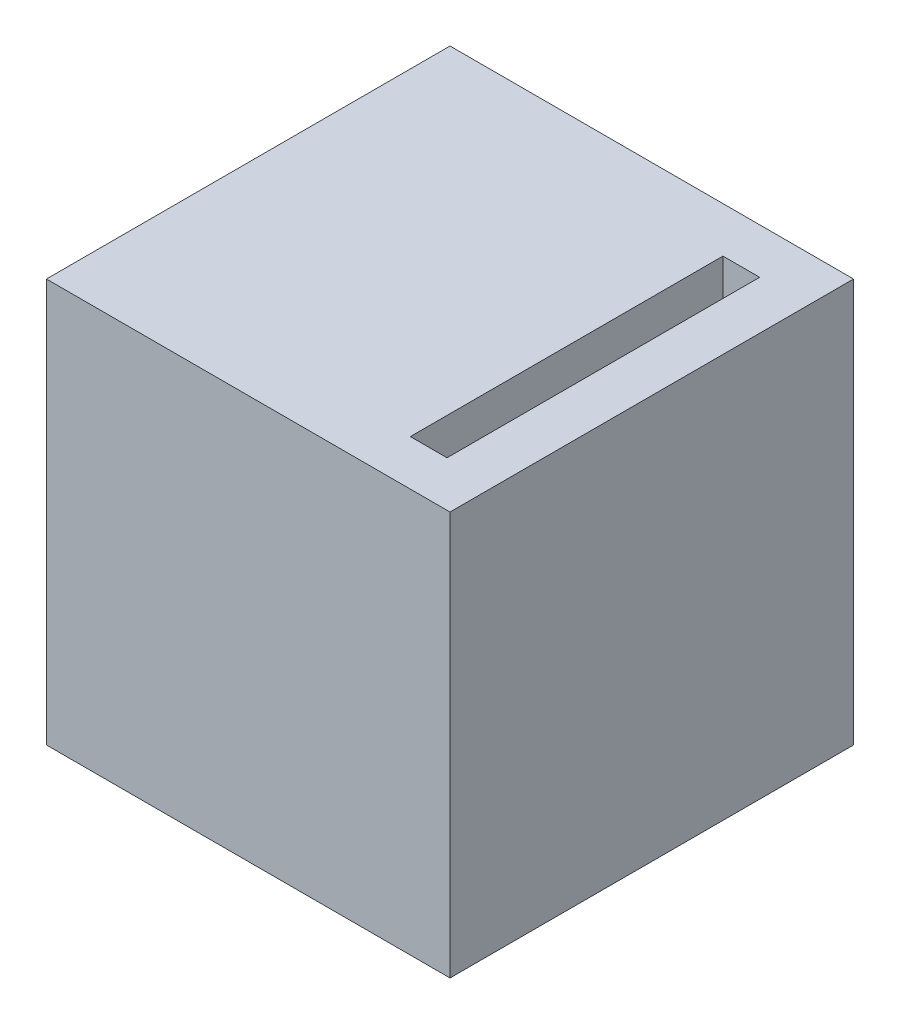
SolidWorks part; units mm, degrees
ref_plane "Front Plane" through (0, 0, 0) normal (0, 0, 1) x (1, 0, 0)
ref_plane "Top Plane" through (0, 0, 0) normal (0, 1, 0) x (1, 0, 0)
ref_plane "Right Plane" through (0, 0, 0) normal (1, 0, 0) x (0, 0, -1)
sketch "Sketch1" plane through (0, 0, 0) normal (0, 1, 0) x (1, 0, 0)
  line L1 (-39.3747, -25.11) -> (-34.3747, -25.11)
  line L2 (-39.3747, -25.11) -> (-39.3747, -30.11)
  line L3 (-39.3747, -30.11) -> (-34.3747, -30.11)
  line L4 (-34.3747, -25.11) -> (-34.3747, -30.11)
extrude "Boss-Extrude1" add sketch "Sketch1" along normal blind 5 contours L2 L1 L4 L3
sketch "Sketch2" plane through (0, 5, 0) normal (0, 1, 0) x (1, 0, 0)
  line L0 (-39.3747, -25.11) -> (-34.3747, -25.11) construction
  line L1 (-35.4296, -25.6733) -> (-34.9747, -25.6733)
  line L2 (-35.4296, -25.6733) -> (-35.4296, -29.5467)
  line L3 (-35.4296, -29.5467) -> (-34.9747, -29.5467)
  line L4 (-34.9747, -25.6733) -> (-34.9747, -29.5467)
  line L6 (-35.4296, -25.6733) -> (-35.4296, -25.11)
  line L7 (-35.4296, -29.5467) -> (-35.4296, -30.11)
  line L8 (-39.3747, -30.11) -> (-34.3747, -30.11) construction
  line L9 (-34.3747, -25.11) -> (-34.3747, -30.11) construction
  dimension "D1" = 0.6
extrude "Cut-Extrude1" cut sketch "Sketch2" against normal blind 4 contours L4 L1 L2 L3
